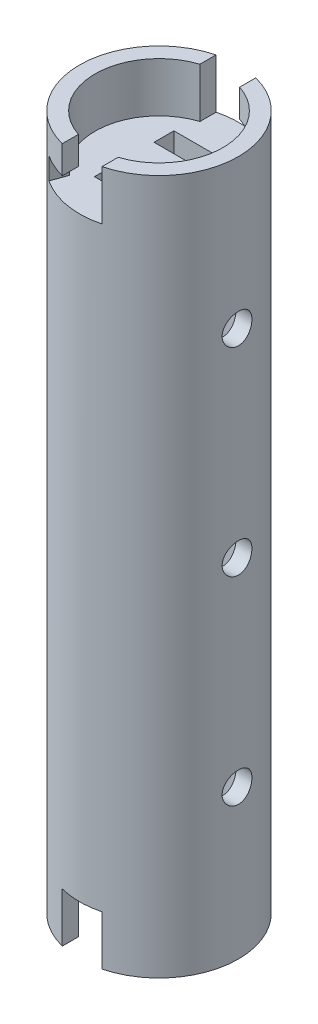
SolidWorks part; units mm, degrees
ref_plane "Front Plane" through (0, 0, 0) normal (0, 0, 1) x (1, 0, 0)
ref_plane "Top Plane" through (0, 0, 0) normal (0, 1, 0) x (1, 0, 0)
ref_plane "Right Plane" through (0, 0, 0) normal (1, 0, 0) x (0, 0, -1)
sketch "Sketch2" plane through (0, 0, 0) normal (0, 1, 0) x (1, 0, 0)
  circle A0 centre (0, 0) radius 10.16
  circle A1 centre (0, 0) radius 8.1788
  dimension "D1" = 20.32
  dimension "D2" = 1.9812
extrude "Boss-Extrude2" add sketch "Sketch2" along normal mid plane 88.9
sketch "Sketch4" plane through (0, 44.45, 0) normal (0, 1, 0) x (1, 0, 0)
  line L0 (-2.54, 9.8374) -> (-2.54, -9.8374)
  line L1 (0, -55) -> (0, 55) construction
  line L2 (2.54, 9.8374) -> (2.54, -9.8374)
  circle A0 centre (0, 0) radius 10.16 construction
  arc A1 (-2.54, -9.8374) -> (2.54, -9.8374) centre (0, 0) ccw
  arc A2 (2.54, 9.8374) -> (-2.54, 9.8374) centre (0, 0) ccw
  dimension "D1" = 5.08
extrude "Cut-Extrude1" cut sketch "Sketch4" against normal blind 6.35
mirror "Mirror1" about plane through (0, 0, 0) normal (0, 1, 0) of "Cut-Extrude1"
sketch "Sketch5" plane through (0, 0, 0) normal (1, 0, 0) x (0, 0, -1)
  line L0 (11.176, 0) -> (-11.176, 0) construction
  circle A0 centre (0, 0) radius 1.905
  circle A1 centre (0, 25.4) radius 1.905
  circle A3 centre (0, -25.4) radius 1.905
  circle A5 centre (0, 50.8) radius 1.905 [skipped]
  dimension "D1" = 3.81
  dimension "D3" = 25.4
  dimension "D2" = 3
extrude "Cut-Extrude3" cut sketch "Sketch5" against normal up to next and the other way blind 13.97
sketch "Sketch6" plane through (0, 44.45, 0) normal (0, 1, 0) x (1, 0, 0)
  line L0 (2.54, 7.7744) -> (2.54, 0) construction
  line L1 (-4.9184, -6.5347) -> (-5.6206, -8.4637)
  line L3 (-55, 0) -> (55, 0) construction
  line L4 (2.54, 0) -> (6.5096, 10.9064) construction
  line L5 (2.54, 7.7744) -> (2.54, 9.8374) construction
  line L6 (2.54, 7.7744) -> (2.54, 9.8374)
  line L7 (5.6206, 8.4637) -> (4.9184, 6.5347)
  line L8 (-2.54, -7.7744) -> (-2.54, 0) construction
  line L9 (-2.54, 0) -> (-6.0633, -9.6802) construction
  line L10 (-2.54, -7.7744) -> (-2.54, -9.8374) construction
  line L11 (-2.54, -7.7744) -> (-2.54, -9.8374)
  arc A0 (2.54, -7.7744) -> (2.54, 7.7744) centre (0, 0) ccw construction
  arc A1 (2.54, -9.8374) -> (2.54, 9.8374) centre (0, 0) ccw construction
  arc A2 (4.9184, 6.5347) -> (2.54, 7.7744) centre (0, 0) ccw
  arc A3 (5.6206, 8.4637) -> (2.54, 9.8374) centre (0, 0) ccw
  arc A4 (-2.54, 7.7744) -> (-2.54, -7.7744) centre (0, 0) ccw construction
  arc A5 (-2.54, 9.8374) -> (-2.54, -9.8374) centre (0, 0) ccw construction
  arc A6 (-4.9184, -6.5347) -> (-2.54, -7.7744) centre (0, 0) ccw
  arc A7 (-5.6206, -8.4637) -> (-2.54, -9.8374) centre (0, 0) ccw
  dimension "D1" = 20
  dimension "D2" = 20
extrude "Cut-Extrude4" cut sketch "Sketch6" against normal blind 2.794 from offset 3.556 offset against normal yes
sketch "Sketch7" plane through (0, 38.1, 0) normal (0, 1, 0) x (1, 0, 0)
  line L0 (0, -55) -> (0, 55) construction
  line L1 (-3.175, 5.08) -> (3.175, 5.08)
  line L2 (-3.175, 5.08) -> (-3.175, 2.54)
  line L3 (-3.175, 2.54) -> (3.175, 2.54)
  line L4 (3.175, 5.08) -> (3.175, 2.54)
  line L5 (-3.175, 5.08) -> (3.175, 2.54) construction
  line L6 (-3.175, 2.54) -> (3.175, 5.08) construction
  line L7 (-55, 0) -> (55, 0) construction
  line L8 (-3.175, -2.54) -> (3.175, -2.54)
  line L9 (3.175, -5.08) -> (3.175, -2.54)
  line L10 (-3.175, -5.08) -> (3.175, -5.08)
  line L11 (-3.175, -5.08) -> (-3.175, -2.54)
  circle A0 centre (0, 0) radius 8.1788
  arc A1 (4.9184, 6.5347) -> (-2.54, 7.7744) centre (0, 0) ccw construction
  point P6 (0, 3.81)
  dimension "D1" = 6.35
  dimension "D2" = 2.54
  dimension "D3" = 5.08
extrude "Boss-Extrude3" add sketch "Sketch7" against normal blind 2.54
